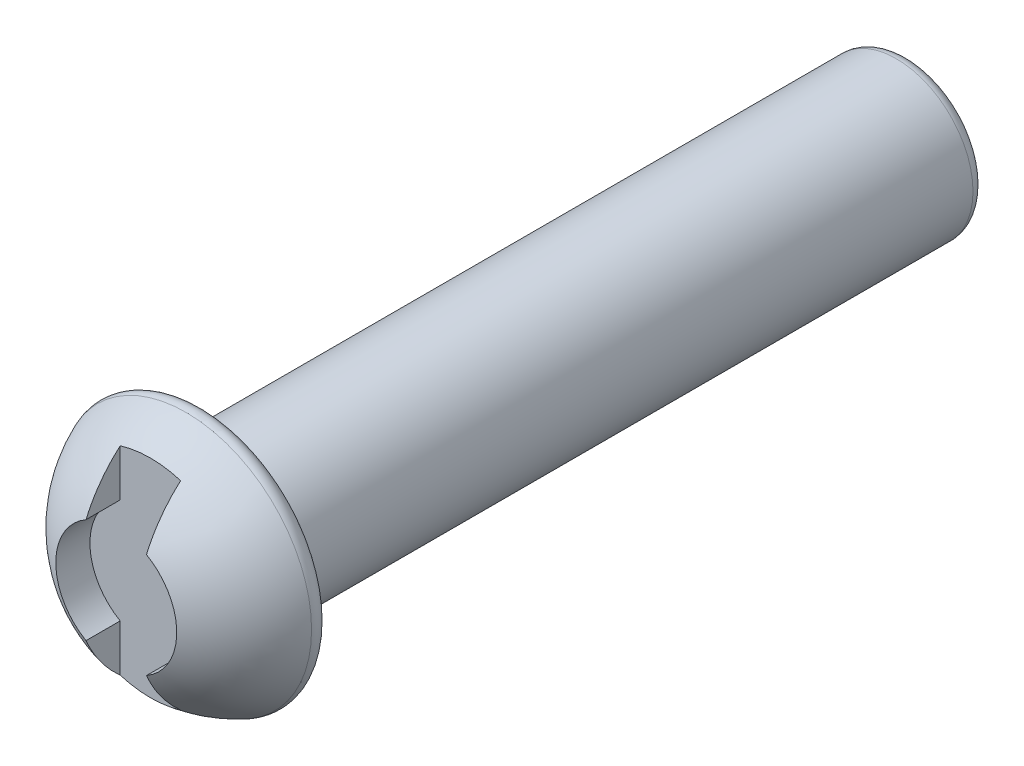
SolidWorks part; units mm, degrees
ref_plane "Front Plane" through (0, 0, 0) normal (0, 0, 1) x (1, 0, 0)
ref_plane "Top Plane" through (0, 0, 0) normal (0, 1, 0) x (1, 0, 0)
ref_plane "Right Plane" through (0, 0, 0) normal (1, 0, 0) x (0, 0, -1)
sketch "Sketch1" plane through (0, 0, 0) normal (1, 0, 0) x (0, 0, -1)
  line L0 (0, 0) -> (10, 0)
  line L1 (10, 0) -> (10, 0.95)
  line L2 (10, 0.95) -> (1.25, 0.95)
  line L3 (1.25, 0.95) -> (1.25, 1.625)
  arc A0 (1.25, 1.625) -> (0, 0) centre (1.6812, 0) ccw
  dimension "D1" = 10
  dimension "D2" = 0.95
  dimension "D3" = 0.675
  dimension "D4" = 1.25
revolve "Revolve1" add sketch "Sketch1" angle 360 about L0
sketch "Sketch2" plane through (0, 0, 0) normal (0, 0, 1) x (1, 0, 0)
  line L0 (-0.375, -0.6495) -> (-0.375, -1.8086)
  line L1 (-0.375, 1.8086) -> (0.375, 1.8086)
  line L2 (-0.375, 1.8086) -> (-0.375, 0.6495)
  line L3 (-0.375, -1.8086) -> (0.375, -1.8086)
  line L4 (0.375, 1.8086) -> (0.375, 0.6495)
  line L7 (0.375, -0.6495) -> (0.375, -1.8086)
  arc A0 (-0.375, 0.6495) -> (-0.375, -0.6495) centre (0, 0) ccw
  arc A1 (0.375, -0.6495) -> (0.375, 0.6495) centre (0, 0) ccw
  point P0 (0, 0)
  dimension "D2" = 1.5
  dimension "D1" = 0.75
extrude "Cut-Extrude1" cut sketch "Sketch2" against normal blind 0.6
fillet "Fillet1" radius 0.15 2 edges at (1.625, 0, -1.25) (0.95, 0, -10)
